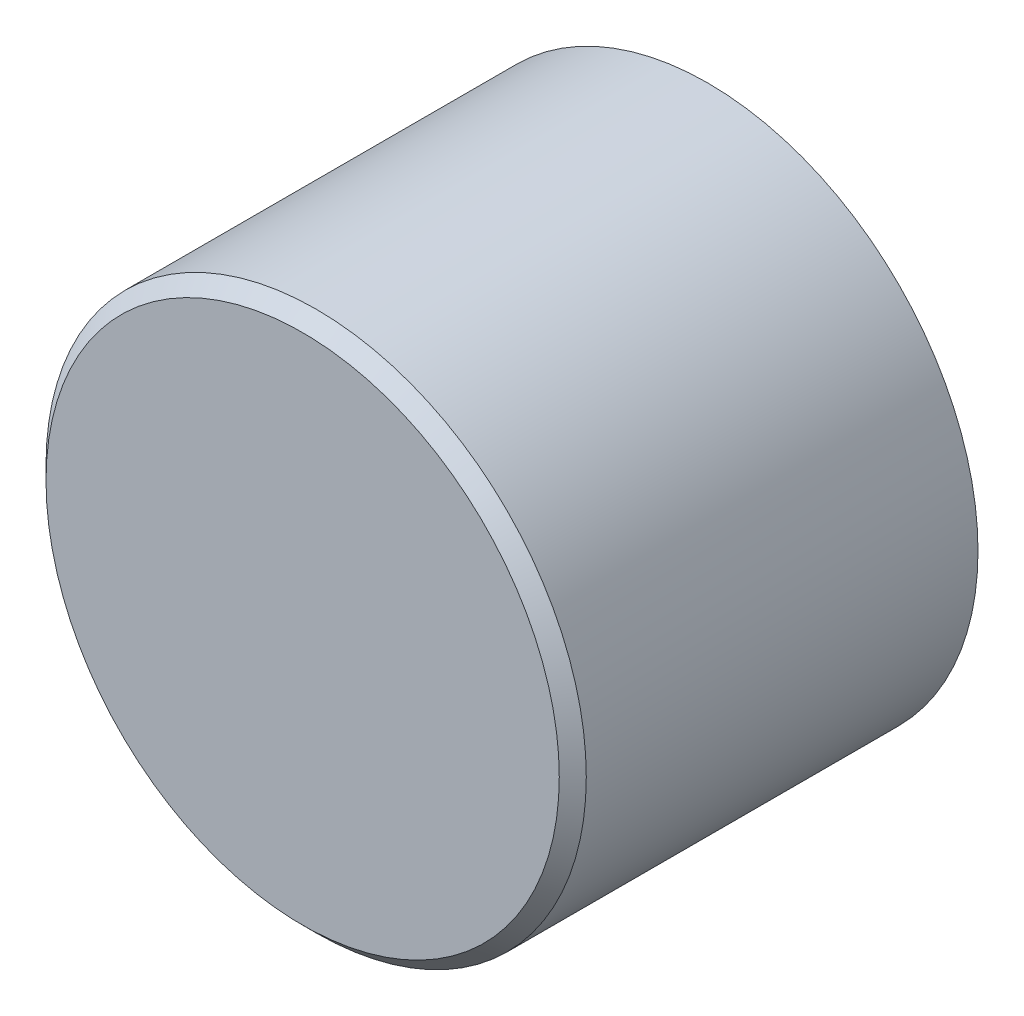
SolidWorks part; units mm, degrees
ref_plane "Front" through (0, 0, 0) normal (0, 0, 1) x (1, 0, 0)
ref_plane "Top" through (0, 0, 0) normal (0, 1, 0) x (1, 0, 0)
ref_plane "Right" through (0, 0, 0) normal (1, 0, 0) x (0, 0, -1)
sketch "COMPONENT_OUTLINE" plane through (0, 0, 0) normal (0, 0, 1) x (1, 0, 0)
  circle A0 centre (0, 0) radius 2
  dimension "D1" = 4
extrude "Extrude1" add sketch "COMPONENT_OUTLINE" along normal blind 3
chamfer "Chamfer1" distance 0.1 angle 45 1 edges at (2, 0, 3)
